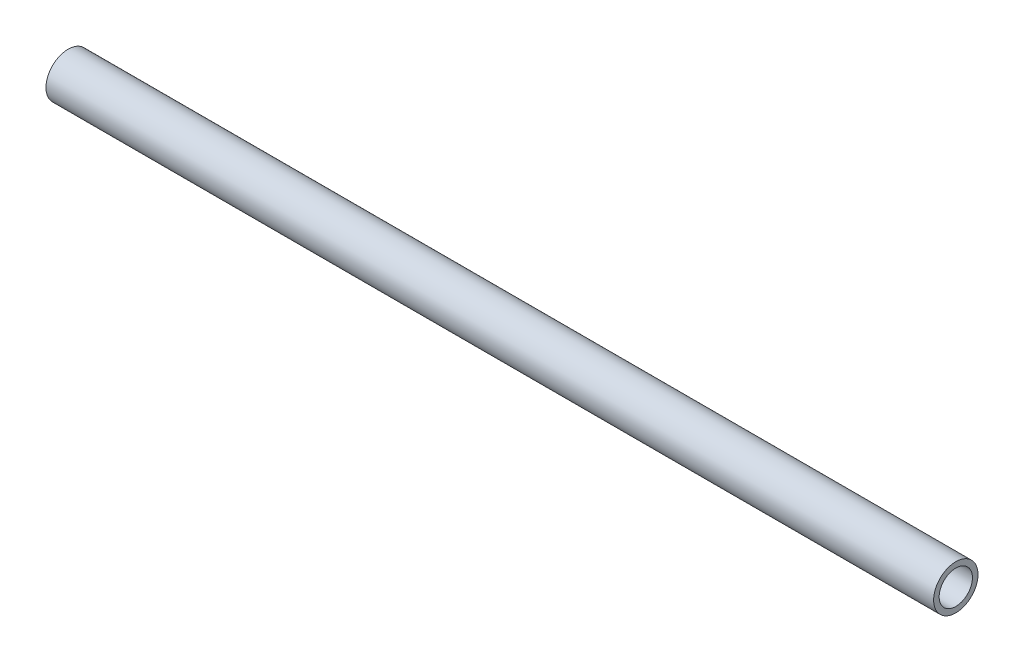
SolidWorks part; units mm, degrees
ref_plane "Front" through (0, 0, 0) normal (0, 0, 1) x (1, 0, 0)
ref_plane "Top" through (0, 0, 0) normal (0, 1, 0) x (1, 0, 0)
ref_plane "Right" through (0, 0, 0) normal (1, 0, 0) x (0, 0, -1)
sketch "Sketch1" plane through (0, 0, 0) normal (1, 0, 0) x (0, 0, -1)
  circle A0 centre (0, 0) radius 12.7
  circle A1 centre (0, 0) radius 9.525
  point P4 (12.7, 0)
  point P5 (9.525, 0)
  dimension "OD" = 25.4
  dimension "ID" = 19.05
  dimension "Wall" = 3.175
extrude "Extrude1" add sketch "Sketch1" along normal mid plane 914.4
sketch "Sketch2" plane through (0, 0, 0) normal (0, 0, 1) x (1, 0, 0)
  line L0 (-457.2, 0) -> (457.2, 0) construction
  line L1 (-457.2, 12.7) -> (-457.2, -12.7) construction
sketch "Sketch3" plane through (-457.2, 0, 0) normal (-1, 0, 0) x (0, 0, 1)
  circle A1 centre (0, 0) radius 12.7
  circle A2 centre (0, 0) radius 12.7
  dimension "D1" = 0
extrude "Cut-Extrude1" cut sketch "Sketch3" against normal offset from surface (406.4 mm away) 508 up to face at (457.2, 0, -12.7)
